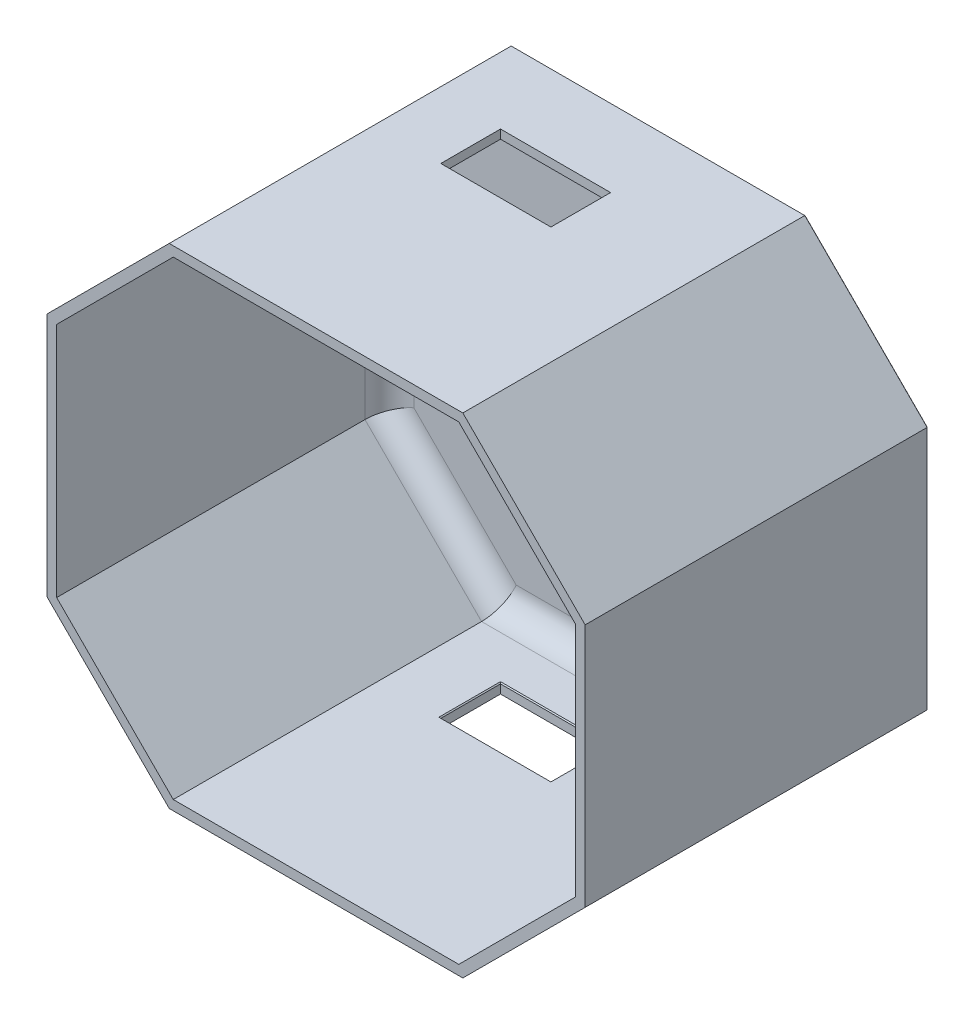
SolidWorks part; units mm, degrees
ref_plane "Alzado" through (0, 0, 0) normal (0, 0, 1) x (1, 0, 0)
ref_plane "Planta" through (0, 0, 0) normal (0, 1, 0) x (1, 0, 0)
ref_plane "Vista lateral" through (0, 0, 0) normal (1, 0, 0) x (0, 0, -1)
sketch "Croquis1" plane through (0, 0, 0) normal (0, 0, 1) x (1, 0, 0)
  line L0 (-55, 0) -> (55, 0) construction
  line L1 (0, 50) -> (0, -50) construction
  line L2 (30, 50) -> (-30, 50)
  line L3 (-30, 50) -> (-55, 25)
  line L4 (-55, 25) -> (-55, -25)
  line L5 (-30, -50) -> (-55, -25)
  line L6 (30, -50) -> (-30, -50)
  line L7 (30, -50) -> (55, -25)
  line L8 (55, 25) -> (55, -25)
  line L9 (30, 50) -> (55, 25)
  point P0 (-33.6315, 50)
  point P5 (-54.3756, 0)
  dimension "D1" = 110
  dimension "D2" = 100
  dimension "D3" = 25
  dimension "D4" = 45
extrude "Saliente-Extruir1" add sketch "Croquis1" along normal blind 70
shell "Vaciado1" thickness 2
sketch "Croquis2" plane through (0, -50, 0) normal (0, -1, 0) x (1, 0, 0)
  line L0 (-30, 22) -> (30, 22) construction
  line L1 (-30, 70) -> (-30, 0) construction
  line L2 (30, 70) -> (30, 0) construction
  line L3 (-29.1716, 2) -> (29.1716, 2) construction
  line L4 (0, 70) -> (0, 0) construction
  line L5 (-30, 70) -> (30, 70) construction
  line L6 (-30, 0) -> (30, 0) construction
  circle A0 centre (0, 22) radius 14.9609 construction
  point P14 (0, 22)
  dimension "D1" = 20
sketch "Croquis4" plane through (0, -50, 0) normal (0, -1, 0) x (1, 0, 0)
  line L0 (-16.4, 28.1) -> (6.1, 28.1)
  line L5 (6.1, 28.1) -> (6.1, 15.9)
  line L6 (-16.4, 15.9) -> (6.1, 15.9)
  line L7 (-16.4, 28.1) -> (-16.4, 15.9)
extrude "Cortar-Extruir1" cut sketch "Croquis4" against normal up to next
ref_plane "Plano1" through (0, 0, 0) normal (0, 1, 0) x (1, 0, 0)
mirror "Simetría1" about plane through (0, 0, 0) normal (0, 1, 0) of "Cortar-Extruir1"
fillet "Redondeo1" radius 5 8 edges at (0, -48, 2) (-41.0858, -36.0858, 2) (-53, 0, 2) (-41.0858, 36.0858, 2) (0, 48, 2) (41.0858, 36.0858, 2) (53, 0, 2) (41.0858, -36.0858, 2)
chamfer "Chaflán1" distance 0.12 angle 45 8 edges at (55, 0, 0) (42.5, 37.5, 0) (0, 50, 0) (-42.5, 37.5, 0) (-55, 0, 0) (-42.5, -37.5, 0) (0, -50, 0) (42.5, -37.5, 0)
chamfer "Chaflán2" distance 0.2 angle 45 8 edges at (6.1, 48, 22) (-5.15, 48, 15.9) (-16.4, 48, 22) (-5.15, 48, 28.1) (-16.4, -48, 22) (-5.15, -48, 15.9) (-5.15, -48, 28.1) (6.1, -48, 22)
